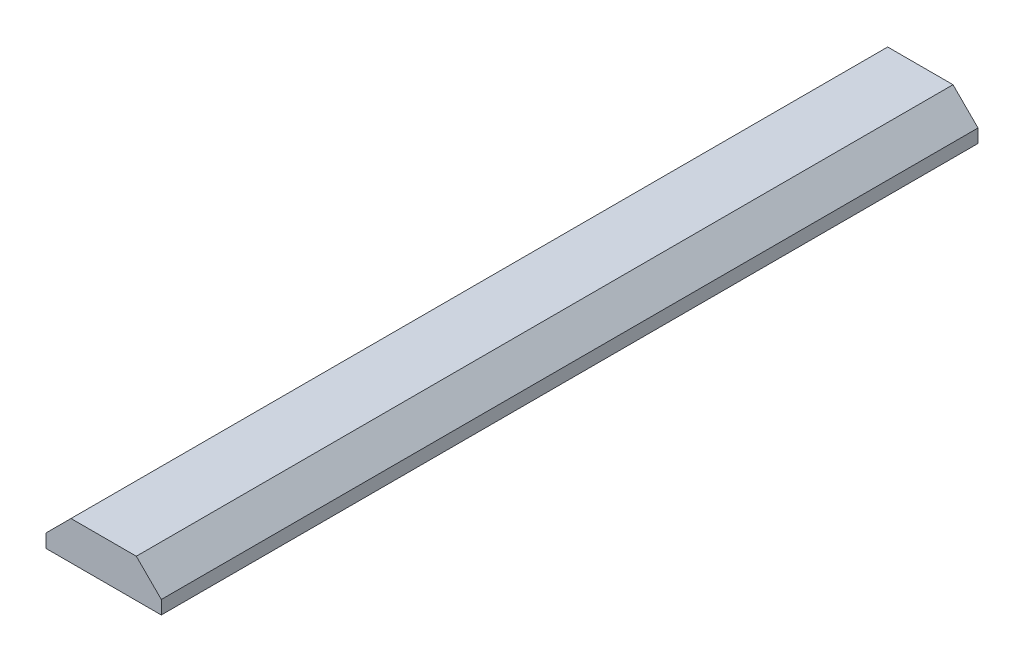
SolidWorks part; units mm, degrees
ref_plane "Ebene vorne" through (0, 0, 0) normal (0, 0, 1) x (1, 0, 0)
ref_plane "Ebene oben" through (0, 0, 0) normal (0, 1, 0) x (1, 0, 0)
ref_plane "Ebene rechts" through (0, 0, 0) normal (1, 0, 0) x (0, 0, -1)
sketch "Skizze1" plane through (0, 0, 0) normal (0, 0, 1) x (1, 0, 0)
  line L0 (0, 0) -> (0, 23680.6173) construction
  line L1 (3.4, 1.8089) -> (-3.4, 1.8089)
  line L2 (-3.4, 1.8089) -> (-6, -0.7911)
  line L3 (-6, -0.7911) -> (-6, -2.1911)
  line L4 (-6, -2.1911) -> (6, -2.1911)
  line L5 (6, -0.7911) -> (6, -2.1911)
  line L6 (3.4, 1.8089) -> (6, -0.7911)
  point P9 (0, -2.1911)
  point P11 (0, 1.8089)
  dimension "D1" = 3.4
  dimension "D2" = 6
  dimension "D3" = 4
  dimension "D4" = 135
extrude "Aufsatz-Linear austragen1" add sketch "Skizze1" along normal blind 85 contours L1 L2 L3 L4 L5 L6
